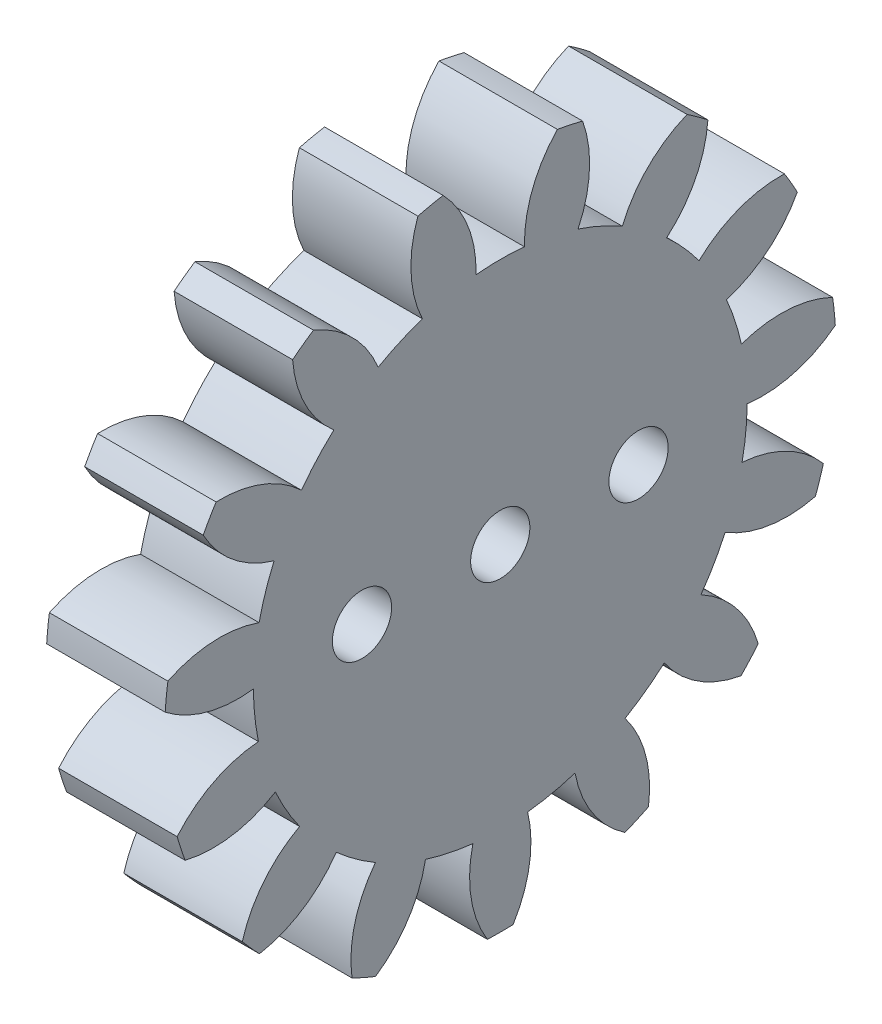
SolidWorks part; units mm, degrees
ref_plane "Plane1" through (0, 0, 0) normal (0, 0, 1) x (1, 0, 0)
ref_plane "Plane2" through (0, 0, 0) normal (0, 1, 0) x (1, 0, 0)
ref_plane "Plane3" through (0, 0, 0) normal (1, 0, 0) x (0, 0, -1)
sketch "HoldingSke" plane through (0, 0, 0) normal (0, 1, 0) x (1, 0, 0)
  line L0 (0, 0) -> (0.483, -0.1294)
  line L1 (-15, 0) -> (100, 0) construction
  line L2 (0, 0) -> (-2.1039, 2.3779)
  line L3 (0, 0) -> (-11.863, 4.5341)
  line L4 (0, 0) -> (8.3417, 2.2352)
  line L5 (0, 0) -> (-46.8476, -17.4728)
  line L6 (0, 0) -> (-4.9738, -3.3558)
  line L7 (-2.1039, 2.3779) -> (8.6586, 51.2059)
  line L8 (-76.2, 54.61) -> (-74.8, 54.61)
  line L9 (-67.7845, 28.3722) -> (-49.3413, 33.142)
  line L10 (-76.2, 71.12) -> (104.1128, 71.12)
  line L11 (0, 0) -> (-6, 0)
  line L12 (-76.2, 101.6) -> (-76.133, 101.6)
  line L13 (24.9733, 27.94) -> (52.9518, 28.4284)
  line L14 (24.9733, 27.94) -> (24.9743, 27.94)
  line L15 (24.9733, 27.94) -> (100.4006, 29.5858)
  line L16 (-63.627, -2) -> (-12.827, -2)
  circle A0 centre (0, 0) radius 4
  circle A1 centre (0, 0) radius 12.499
  circle A2 centre (0, 0) radius 37.5
  circle A3 centre (0, 0) radius 4
  dimension "MHD" = 24.998
  dimension "Hub_dia" = 75
  dimension "Bore" = 8
  dimension "MBD" = 8
  dimension "Num_teeth" = 15
  dimension "Pitch" = 0.5
  dimension "Overall_len" = 50
  dimension "Show_teeth" = 15
  dimension "Thickness" = 6
  dimension "OAL" = 50.0001
  dimension "T_dim" = 1.4
  dimension "Ap" = 14.5
  dimension "H" = 19.05
  dimension "Pitch_radius" = 180.3128
  dimension "Width" = 6
  dimension "Backlash" = 0.067
  dimension "Addendum_fac" = 1
  dimension "Dedendum_fac" = 1.25
  dimension "Clearance_fac" = 0.25
  dimension "Dedendum_add" = 0.001
  dimension "Module" = 2
sketch "BasProSke" plane through (0, 0, 0) normal (0, 1, 0) x (1, 0, 0)
  line L0 (-10, 0) -> (60, 0) construction
  line L1 (0, 0) -> (0, 17)
  line L2 (0, 0) -> (6, 0)
  line L3 (6, 0) -> (6, 17)
  line L4 (6, 17) -> (0, 17)
  dimension "Thickness" = 6
  dimension "Diameter" = 34
revolve "Base-Revolve" add sketch "BasProSke" angle 360 about L0
sketch "TooCutSke" plane through (0, 0, 0) normal (1, 0, 0) x (0, 0, -1)
  line L1 (0, 0) -> (0, 107) construction
  line L2 (0, 0) -> (-1.6851, 14.905) construction
  line L3 (0, 0) -> (-6.2081, 29.2069) construction
  line L4 (-1.6851, 14.905) -> (-3.1041, 14.6034) construction
  arc A0 (1.2259, 12.4387) -> (-1.2259, 12.4387) centre (0, 0) ccw
  arc A1 (2.9155, 16.7739) -> (-2.9155, 16.7739) centre (0, 0) ccw
  circle A2 centre (0, 0) radius 15 construction
  circle A3 centre (0, 0) radius 14.5222 construction
  arc A4 (-1.2259, 12.4387) -> (-2.9155, 16.7739) centre (-7.2238, 12.5981) ccw
  arc A5 (2.9155, 16.7739) -> (1.2259, 12.4387) centre (7.2238, 12.5981) ccw
  dimension "Root_dia" = 24.998
  dimension "Overcut_dia" = 34.0508
  dimension "Pitch_dia" = 30
  dimension "Base_dia" = 29.0444
  dimension "Flank_rad" = 6
  dimension "Half_ang" = 12
  dimension "Half_CT" = 1.4507
extrude "ToothCut" cut sketch "TooCutSke" along normal through all
fillet "Breaks" [suppressed] radius 0.04
fillet "RootFillets" [suppressed] radius 0.501
pattern_circular "TeethCuts" count 15 every 24 about axis through (-10, 0, 0) along (1, 0, 0) of "ToothCut", "RootFillets", "Breaks"
sketch "HubNeaOneSke" plane through (0, 0, 0) normal (-1, 0, 0) x (0, 0, 1)
  circle A0 centre (0, 0) radius 12.499
  dimension "Diameter" = 24.998
extrude "HubNearOne" [suppressed] add sketch "HubNeaOneSke" along normal blind 44.0001
sketch "HubNeaBotSke" plane through (0, 0, 0) normal (-1, 0, 0) x (0, 0, 1)
  circle A0 centre (0, 0) radius 12.499
  dimension "Diameter" = 24.998
extrude "HubNearBoth" [suppressed] add sketch "HubNeaBotSke" along normal blind 22
ref_plane "FarPln" through (6, 0, 0) normal (1, 0, 0) x (0, 0, -1)
sketch "HubFarSke" plane through (6, 0, 0) normal (1, 0, 0) x (0, 0, -1)
  circle A0 centre (0, 0) radius 12.499
  dimension "Diameter" = 24.998
extrude "HubFar" [suppressed] add sketch "HubFarSke" along normal blind 22
sketch "BorSke" plane through (0, 0, 0) normal (1, 0, 0) x (0, 0, -1)
  circle A0 centre (0, 0) radius 4
  dimension "Diameter" = 8
extrude "Bore" cut sketch "BorSke" along normal mid plane 100.0001
sketch "KeySke" plane through (0, 0, 0) normal (1, 0, 0) x (0, 0, -1)
  line L0 (-1.5, 0) -> (-1.5, 5.4)
  line L1 (-1.5, 5.4) -> (1.5, 5.4)
  line L2 (1.5, 5.4) -> (1.5, 0)
  line L3 (0, 0) -> (0, 34) construction
  line L4 (-1.5, 0) -> (1.5, 0)
  dimension "Offset" = 5.4
  dimension "Width" = 3
extrude "Keyway" [suppressed] cut sketch "KeySke" along normal mid plane 100.0001
pattern_circular "Keyway2" [suppressed] count 2 every 90 about axis through (-10, 0, 0) along (1, 0, 0)
sketch "Croquis1" plane through (6, 0, 0) normal (1, 0, 0) x (0, 0, -1)
  circle A0 centre (0, 0) radius 4
  circle A1 centre (0, 0) radius 1.5
extrude "Saliente-Extruir1" add sketch "Croquis1" against normal blind 6
sketch "Croquis2" plane through (6, 0, 0) normal (1, 0, 0) x (0, 0, -1)
  circle A0 centre (-7, 0) radius 1.5
  circle A1 centre (7, 0) radius 1.5
  circle A2 centre (0, 0) radius 1.5 construction
  dimension "D1" = 7
  dimension "D2" = 7
extrude "Cortar-Extruir1" cut sketch "Croquis2" against normal blind 6
equation "' \"Module@HoldingSke\" = 6.35"
equation "' \"Num_teeth@HoldingSke\" = 12"
equation "' \"Ap@HoldingSke\" =  20"
equation "' \"Ap@HoldingSke\" = 20"
equation "' \"Width@HoldingSke\" = 0.5 * 25.4"
equation "' \"Hub_dia@HoldingSke\"= 1 * 25.4"
equation "' \"Hub_dia@HoldingSke\" = 1 * 25.4"
equation "' \"Overall_len@HoldingSke\" = 1.0 * 25.4"
equation "' \"Bore@HoldingSke\" = 0.75 * 25.4"
equation "' \"T_dim@HoldingSke\" = 0.1 * 25.4"
equation "' \"Width@KeySke\" = 0.25 * 25.4"
equation "' \"Show_teeth@HoldingSke\" = 13"
equation "' \"Backlash@HoldingSke\" = 0.009 * 25.4"
equation "' \"Addendum_fac@HoldingSke\" = 1.0"
equation "' \"Dedendum_fac@HoldingSke\" = 1.25"
equation "' \"Dedendum_add@HoldingSke\" = 0.00005 * 25.4"
equation "' \"Clearance_fac@HoldingSke\" = 0.25"
equation "\"Pitch@HoldingSke\" = 1 / \"Module@HoldingSke\""
equation "\"Overcut_dia@TooCutSke\" = (\"Num_teeth@HoldingSke\" + 2 * \"Addendum_fac@HoldingSke\") / \"Pitch@HoldingSke\" + 0.002 * 25.4"
equation "\"Pitch_dia@TooCutSke\" = \"Num_teeth@HoldingSke\" / \"Pitch@HoldingSke\""
equation "\"Base_dia@TooCutSke\" = \"Num_teeth@HoldingSke\" / \"Pitch@HoldingSke\" * cos((\"Ap@HoldingSke\"  * 3.14159265 / 180))"
equation "\"Root_dia@TooCutSke\" = (\"Num_teeth@HoldingSke\" + 2) / \"Pitch@HoldingSke\" - 2 * (\"Addendum_fac@HoldingSke\" + \"Dedendum_fac@HoldingSke\") / \"Pitch@HoldingSke\" - \"Dedendum_add@HoldingSke\" * 2"
equation "\"Half_ang@TooCutSke\" = 180 / \"Num_teeth@HoldingSke\""
equation "\"Half_CT@TooCutSke\" = \"Num_teeth@HoldingSke\" / \"Pitch@HoldingSke\" * sin((3.14159265 / 2 / \"Num_teeth@HoldingSke\")) / 2 - 7 * \"Backlash@HoldingSke\" / 4"
equation "\"Flank_rad@TooCutSke\" = \"Num_teeth@HoldingSke\" / \"Pitch@HoldingSke\" / 5"
equation "\"Radius@RootFillets\" = \"Clearance_fac@HoldingSke\" / \"Pitch@HoldingSke\" + \"Dedendum_add@HoldingSke\""
equation "\"Break_rad@Breaks\" = 0.02 / \"Pitch@HoldingSke\""
equation "\"Thickness@HoldingSke\" = \"Width@HoldingSke\""
equation "\"OAL@HoldingSke\" = \"Thickness@HoldingSke\""
equation "\"MHD@HoldingSke\" = (\"Num_teeth@HoldingSke\" + 2) / \"Pitch@HoldingSke\" - 2 * (\"Addendum_fac@HoldingSke\" + \"Dedendum_fac@HoldingSke\")  / \"Pitch@HoldingSke\" - \"Dedendum_add@HoldingSke\" * 2"
equation "\"MBD@HoldingSke\" = (\"Num_teeth@HoldingSke\" + 2) / \"Pitch@HoldingSke\" - 2 * (\"Addendum_fac@HoldingSke\" + \"Dedendum_fac@HoldingSke\")  / \"Pitch@HoldingSke\" - \"Dedendum_add@HoldingSke\" * 2 - 0.002 * 25.4"
equation "\"MHD@HoldingSke\" = ((sgn( \"MHD@HoldingSke\" - \"Hub_dia@HoldingSke\" )-1)*( \"MHD@HoldingSke\" - \"Hub_dia@HoldingSke\" ))/-2+ \"Hub_dia@HoldingSke\""
equation "\"MBD@HoldingSke\" = ((sgn( \"MBD@HoldingSke\" - \"Bore@HoldingSke\" )-1)*( \"MBD@HoldingSke\" - \"Bore@HoldingSke\" ))/-2+ \"Bore@HoldingSke\""
equation "\"OAL@HoldingSke\" = ((sgn( \"OAL@HoldingSke\" - \"Overall_len@HoldingSke\" )+1)*( \"OAL@HoldingSke\" - \"Overall_len@HoldingSke\" ))/2 + \"Overall_len@HoldingSke\" + 0.000002 * 25.4"
equation "\"Num_teeth@TeethCuts\" = int( \"Show_teeth@HoldingSke\" ) + 1"
equation "\"Num_teeth@TeethCuts\" = ((sgn( \"Num_teeth@TeethCuts\" - \"Num_teeth@HoldingSke\" )-1)*( \"Num_teeth@TeethCuts\" - \"Num_teeth@HoldingSke\" ))/-2+ \"Num_teeth@HoldingSke\""
equation "\"Num_teeth@TeethCuts\" = ((sgn( \"Num_teeth@TeethCuts\" - 2.0)+1)*( \"Num_teeth@TeethCuts\" - 2.0))/2 +2.0"
equation "\"Angle@TeethCuts\" = 360.0 / \"Num_teeth@HoldingSke\""
equation "\"Diameter@BasProSke\" = (\"Num_teeth@HoldingSke\" + 2 * \"Addendum_fac@HoldingSke\") / \"Pitch@HoldingSke\""
equation "\"Thickness@BasProSke\"  = \"Thickness@HoldingSke\""
equation "' \"Fillet_rad@BasProSke\" =  \"Thickness@HoldingSke\" * 0.05"
equation "' \"Fillet_rad@BasProSke\" = \"Thickness@HoldingSke\" * 0.05"
equation "\"MHD@HoldingSke\" = ((sgn( \"MHD@HoldingSke\" - \"Root_dia@TooCutSke\" )-1)*( \"MHD@HoldingSke\" - \"Root_dia@TooCutSke\" ))/-2+ \"Root_dia@TooCutSke\""
equation "\"Diameter@HubNeaOneSke\" = \"MHD@HoldingSke\""
equation "\"Length@HubNearOne\" = \"OAL@HoldingSke\" - \"Thickness@BasProSke\""
equation "\"Diameter@HubNeaBotSke\" = \"MHD@HoldingSke\""
equation "\"Length@HubNearBoth\" = ( \"OAL@HoldingSke\" - \"Thickness@BasProSke\" ) / 2.0"
equation "\"Thickness@FarPln\" = \"Thickness@BasProSke\""
equation "\"Diameter@HubFarSke\" = \"MHD@HoldingSke\""
equation "\"Length@HubFar\" = ( \"OAL@HoldingSke\" - \"Thickness@BasProSke\" ) / 2.0"
equation "\"Diameter@BorSke\" = \"MBD@HoldingSke\""
equation "\"D1@Bore\" = \"OAL@HoldingSke\" * 2.0"
equation "\"D1@Keyway\" = \"OAL@HoldingSke\" * 2.0"
equation "\"Offset@KeySke\" = \"T_dim@HoldingSke\" + \"MBD@HoldingSke\" / 2.0"
